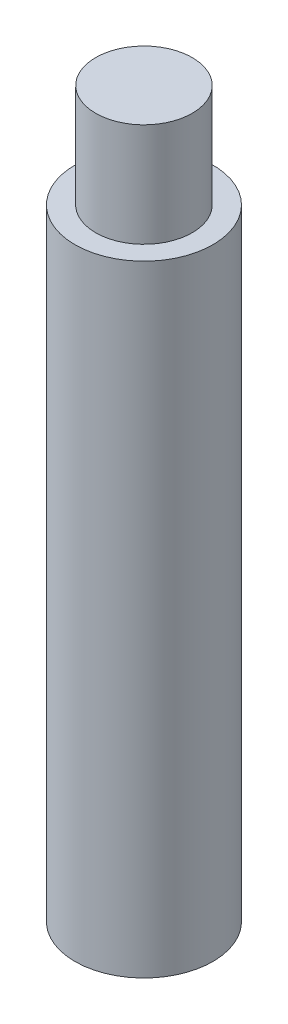
SolidWorks part; units mm, degrees
ref_plane "前视基准面" through (0, 0, 0) normal (0, 0, 1) x (1, 0, 0)
ref_plane "上视基准面" through (0, 0, 0) normal (0, 1, 0) x (1, 0, 0)
ref_plane "右视基准面" through (0, 0, 0) normal (1, 0, 0) x (0, 0, -1)
sketch "草图1" plane through (0, 0, 0) normal (0, 1, 0) x (1, 0, 0)
  circle A0 centre (0, 0) radius 2
extrude "凸台-拉伸1" add sketch "草图1" against normal blind 18
sketch "草图2" plane through (0, 0, 0) normal (0, 1, 0) x (1, 0, 0)
  circle A0 centre (0, 0) radius 1.4
extrude "凸台-拉伸2" add sketch "草图2" along normal blind 3
cosmetic thread "装饰螺纹线1" parameters "D1"=3, "D2"=2.013
hole_wizard "M3 螺纹孔1" positions "3D草图1" profile "草图3" tap size "M3" standard "GB"
sketch3d "3D草图1"
  line L0 (0, -18, 0) -> (0, 0, 0) construction
  point P0 (0, -18, 0)
sketch "草图3" plane through (0, -18, 0) normal (1, 0, 0) x (0, 0, -1)
  line L0 (0, 0) -> (0, 8.2511)
  line L1 (0, 8.2511) -> (1.25, 7.5)
  line L2 (1.25, 7.5) -> (1.25, 0)
  line L5 (1.25, 0) -> (0, 0)
  line L10 (0, 8.2511) -> (-1.25, 7.5) construction
  line L11 (0, -6.35) -> (0, 107.95) construction
  dimension "螺纹孔钻头直径" = 2.5
  dimension "螺纹孔钻头深度" = 7.5
  dimension "导头角度" = 118
cosmetic thread "孔螺蚊线1" parameters "D1"=5, "D2"=3
